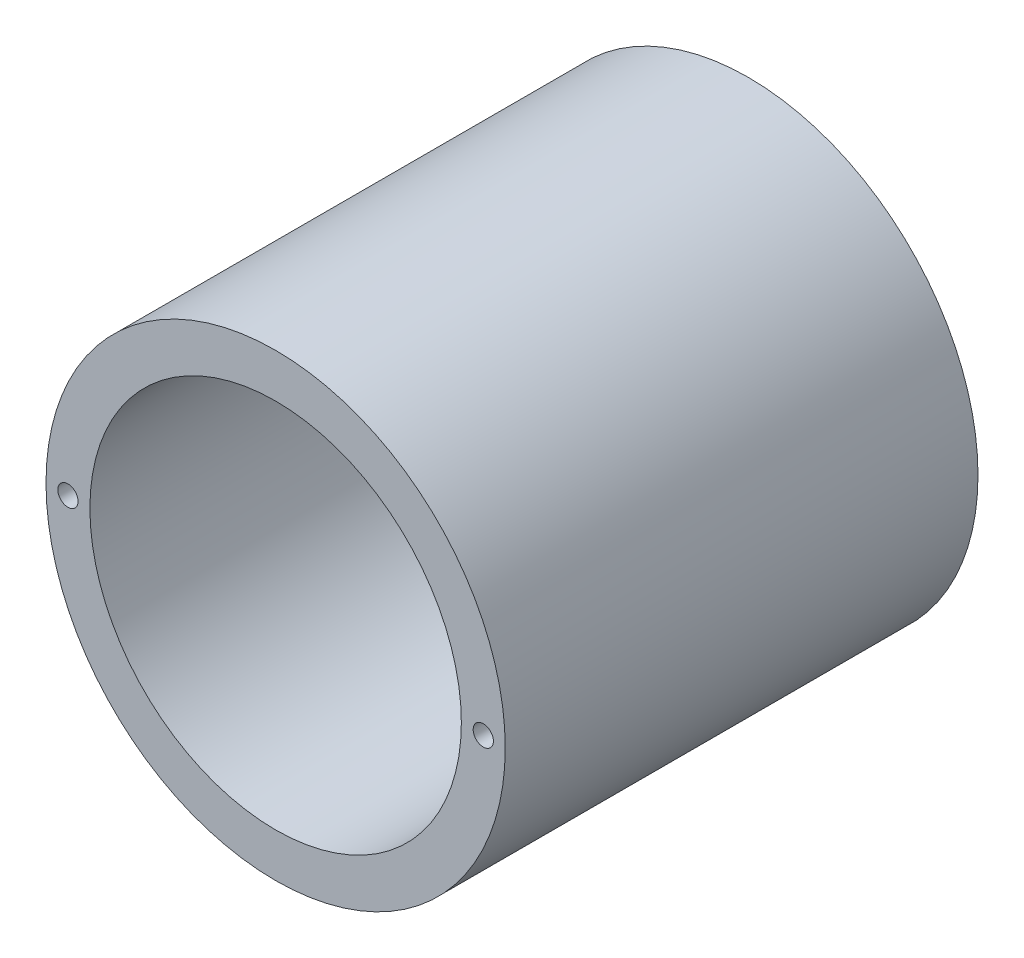
SolidWorks part; units mm, degrees
material "AISI 1020"
ref_plane "Front Plane" through (0, 0, 0) normal (0, 0, 1) x (1, 0, 0)
ref_plane "Top Plane" through (0, 0, 0) normal (0, 1, 0) x (1, 0, 0)
ref_plane "Right Plane" through (0, 0, 0) normal (1, 0, 0) x (0, 0, -1)
sketch "Sketch5" plane through (0, 0, 0) normal (0, 0, 1) x (1, 0, 0)
  circle A1 centre (0, 0) radius 34
  dimension "D2" = 68
extrude "Boss-Extrude1" add sketch "Sketch5" along normal blind 70
sketch "Sketch6" plane through (0, 0, 70) normal (0, 0, 1) x (1, 0, 0)
  circle A0 centre (0, 0) radius 27.5
  dimension "D1" = 55
extrude "Cut-Extrude1" cut sketch "Sketch6" against normal blind 40
sketch "Sketch7" plane through (0, 0, 30) normal (0, 0, 1) x (1, 0, 0)
  circle A0 centre (0, 0) radius 21.5
  dimension "D1" = 43
extrude "Cut-Extrude2" cut sketch "Sketch7" against normal blind 10
sketch "Sketch8" plane through (0, 0, 0) normal (0, 0, -1) x (-1, 0, 0)
  circle A0 centre (0, 0) radius 12
  dimension "D1" = 24
extrude "Cut-Extrude3" cut sketch "Sketch8" against normal blind 20
sketch "Sketch9" plane through (0, 0, 70) normal (0, 0, 1) x (1, 0, 0)
  circle A0 centre (-30.75, 0) radius 1.5
  circle A1 centre (30.75, 0) radius 1.5
  circle A7 centre (0, 0) radius 34 construction
  dimension "D1" = 3
  dimension "D2" = 3
  dimension "D3" = 30.75
  dimension "D4" = 30.75
  dimension "D5" = 61.5
extrude "Cut-Extrude4" cut sketch "Sketch9" against normal blind 20
hole_wizard "M5x0.8 Tapped Hole1" positions "Sketch13" profile "Sketch14" tap size "M5x0.8" standard "ANSI Metric"
sketch "Sketch13" plane through (0, 0, 0) normal (0, 0, -1) x (-1, 0, 0)
  point P0 (-10, 22)
  point P2 (10, 22)
  point P4 (10, -22)
  point P6 (-10, -22)
  point P14 (-52.1859, 33.2463)
  dimension "D1" = 22
  dimension "D2" = 10
  dimension "D3" = 22
  dimension "D4" = 10
  dimension "D5" = 22
  dimension "D6" = 10
  dimension "D7" = 22
  dimension "D8" = 10
sketch "Sketch14" plane through (10, 22, 0) normal (1, 0, 0) x (0, 1, 0)
  line L0 (0, 0) -> (0, 11.2618)
  line L1 (0, 11.2618) -> (2.1, 10)
  line L2 (2.1, 10) -> (2.1, 0)
  line L5 (2.1, 0) -> (0, 0)
  line L10 (0, 11.2618) -> (-2.1, 10) construction
  line L11 (0, -6.35) -> (0, 107.95) construction
  dimension "Tap Drill Dia." = 4.2
  dimension "Tap Drill Depth" = 10
  dimension "Drill Angle" = 118
cosmetic thread "Hole Thread1" parameters "D1"=10, "D2"=5
cosmetic thread "Hole Thread2" parameters "D1"=10, "D2"=5
cosmetic thread "Hole Thread3" parameters "D1"=10, "D2"=5
cosmetic thread "Hole Thread4" parameters "D1"=10, "D2"=5
